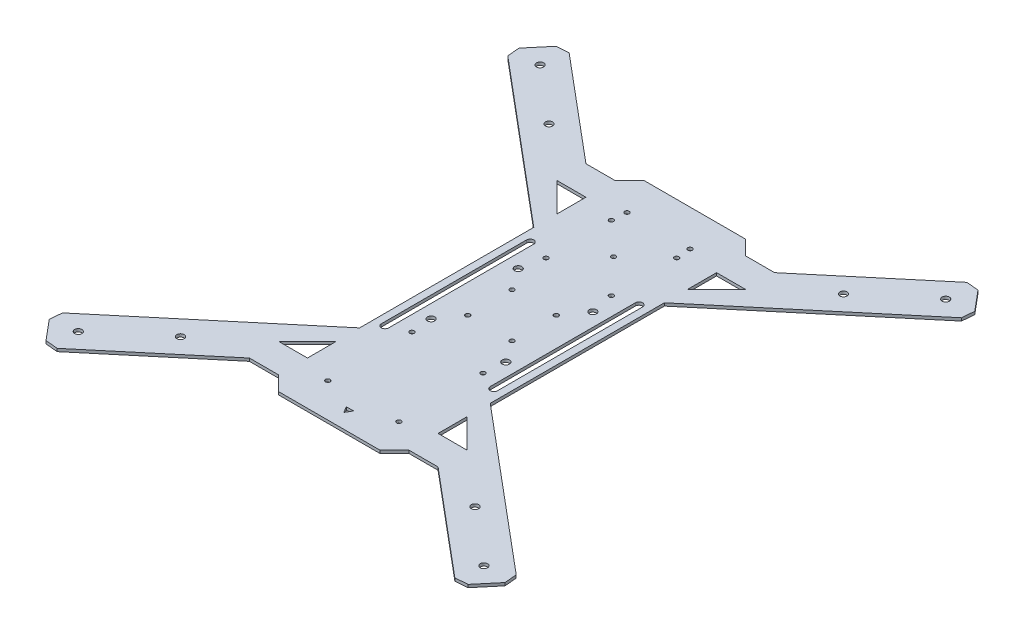
SolidWorks part; units mm, degrees
material "Thornel Mat VMA"
ref_plane "Ön Düzlem" through (0, 0, 0) normal (0, 0, 1) x (1, 0, 0)
ref_plane "Üst Düzlem" through (0, 0, 0) normal (0, 1, 0) x (1, 0, 0)
ref_plane "Sağ Düzlem" through (0, 0, 0) normal (1, 0, 0) x (0, 0, -1)
sketch "Çizim2" plane through (0, 0, 0) normal (0, 1, 0) x (1, 0, 0)
  line L0 (-45, 60) -> (-160.8881, 157.2416)
  line L1 (-45, 100) -> (45, 100)
  line L2 (-45, 100) -> (-45, -100)
  line L3 (-45, -100) -> (45, -100)
  line L4 (45, 100) -> (45, -100)
  line L5 (-160.8881, 157.2416) -> (-141.6044, 180.223)
  line L6 (-141.6044, 180.223) -> (-65, 115.9442)
  line L7 (-65, 115.9442) -> (-45, 115.9442)
  line L8 (-45, 115.9442) -> (-35, 125.9442)
  line L9 (-35, 125.9442) -> (35, 125.9442)
  line L10 (35, 125.9442) -> (45, 115.9442)
  line L11 (45, 115.9442) -> (65, 115.9442)
  line L12 (65, 115.9442) -> (141.6044, 180.223)
  line L13 (141.6044, 180.223) -> (160.8881, 157.2416)
  line L14 (160.8881, 157.2416) -> (45, 60)
  line L15 (0, 0) -> (-44.0753, 0) construction
  line L16 (160.8881, -157.2416) -> (45, -60)
  line L17 (141.6044, -180.223) -> (160.8881, -157.2416)
  line L18 (65, -115.9442) -> (141.6044, -180.223)
  line L19 (45, -115.9442) -> (65, -115.9442)
  line L20 (35, -125.9442) -> (45, -115.9442)
  line L21 (-35, -125.9442) -> (35, -125.9442)
  line L22 (-45, -115.9442) -> (-35, -125.9442)
  line L23 (-65, -115.9442) -> (-45, -115.9442)
  line L24 (-141.6044, -180.223) -> (-65, -115.9442)
  line L25 (-160.8881, -157.2416) -> (-141.6044, -180.223)
  line L26 (-45, -60) -> (-160.8881, -157.2416)
  dimension "D1" = 200
  dimension "D2" = 90
  dimension "D3" = 130
  dimension "D4" = 130
  dimension "D5" = 30
  dimension "D6" = 100
  dimension "D7" = 100
  dimension "D8" = 45
  dimension "D9" = 100
  dimension "D10" = 130
  dimension "D11" = 135
  dimension "D12" = 135
  dimension "D13" = 10
  dimension "D14" = 40
  dimension "D15" = 40
extrude "Yükseklik-Ekstrüzyon2" add sketch "Çizim2" along normal blind 2
sketch "Çizim3" plane through (0, 2, 0) normal (0, 1, 0) x (1, 0, 0)
  line L0 (-35, 125.9442) -> (35, 125.9442) construction
  circle A0 centre (-22.5, 90.9442) radius 1.55
  circle A1 centre (22.5, 90.9442) radius 1.55
  circle A2 centre (-22.5, 45.9442) radius 1.55
  circle A3 centre (22.5, 45.9442) radius 1.55
  circle A4 centre (-15.25, 15.25) radius 1.55
  circle A5 centre (15.25, 15.25) radius 1.55
  circle A6 centre (15.25, -15.25) radius 1.55
  circle A7 centre (-15.25, -15.25) radius 1.55
  dimension "D1" = 45
  dimension "D2" = 45
  dimension "D3" = 45
  dimension "D6" = 3.1
  dimension "D7" = 3.1
  dimension "D8" = 3.1
  dimension "D9" = 3.1
  dimension "D10" = 30.5
  dimension "D12" = 3.1
  dimension "D13" = 3.1
  dimension "D14" = 3.1
  dimension "D15" = 3.1
  dimension "D16" = 15.25
  dimension "D17" = 15.25
  dimension "D4" = 35
  dimension "D5" = 22.5
  dimension "D11" = 30.5
extrude "Kes-Ekstrüzyon1" cut sketch "Çizim3" against normal blind 2
sketch "Çizim4" plane through (0, 2, 0) normal (0, 1, 0) x (1, 0, 0)
  line L0 (-2.5, -111.6141) -> (0, -115.9442)
  line L1 (0, -115.9442) -> (2.5, -111.6141)
  line L2 (2.5, -111.6141) -> (-2.5, -111.6141)
  line L3 (-35, -125.9442) -> (35, -125.9442) construction
  dimension "D1" = 5
  dimension "D2" = 5
  dimension "D3" = 5
  dimension "D4" = 10
extrude "Kes-Ekstrüzyon2" cut sketch "Çizim4" against normal up to vertex (2 mm away) up to point (0, 0, 0)
sketch "Çizim5" plane through (0, 2, 0) normal (0, 1, 0) x (1, 0, 0)
  line L0 (-65, 95.9442) -> (-45, 95.9442)
  line L1 (-45, 95.9442) -> (-45, 75.9442)
  line L2 (-45, 75.9442) -> (-65, 95.9442)
  line L3 (-65, 115.9442) -> (-45, 115.9442) construction
  line L4 (0, 0) -> (0, 125.9442) construction
  line L5 (-35, 125.9442) -> (35, 125.9442) construction
  line L6 (0, 0) -> (-45, 0) construction
  line L7 (-45, 60) -> (-45, -60) construction
  line L8 (45, 75.9442) -> (65, 95.9442)
  line L9 (45, 95.9442) -> (45, 75.9442)
  line L10 (65, 95.9442) -> (45, 95.9442)
  line L11 (65, -95.9442) -> (45, -95.9442)
  line L12 (45, -95.9442) -> (45, -75.9442)
  line L13 (45, -75.9442) -> (65, -95.9442)
  line L14 (-45, -75.9442) -> (-65, -95.9442)
  line L15 (-45, -95.9442) -> (-45, -75.9442)
  line L16 (-65, -95.9442) -> (-45, -95.9442)
  dimension "D1" = 20
  dimension "D2" = 20
  dimension "D3" = 20
  dimension "D4" = 45
extrude "Kes-Ekstrüzyon3" cut sketch "Çizim5" against normal blind 20
chamfer "Pah1" distance 6 angle 45 8 edges at (160.8881, 1, -157.2416) (141.6044, 1, -180.223) (-141.6044, 1, -180.223) (-160.8881, 1, -157.2416) (-160.8881, 1, 157.2416) (-141.6044, 1, 180.223) (160.8881, 1, 157.2416) (141.6044, 1, 180.223)
sketch "Çizim6" plane through (0, 2, 0) normal (0, 1, 0) x (1, 0, 0)
  line L0 (-157.0313, 161.8379) -> (-145.4612, 175.6267) construction
  line L1 (-45, 60) -> (-156.2918, 153.3849) construction
  line L2 (0, 0) -> (0, 125.9442) construction
  line L3 (-35, 125.9442) -> (35, 125.9442) construction
  line L4 (0, 0) -> (-45, 0) construction
  line L5 (-45, 60) -> (-45, -60) construction
  line L6 (65, 115.9442) -> (137.0082, 176.3662) construction
  line L7 (145.4612, 175.6267) -> (157.0313, 161.8379) construction
  line L8 (-45, -60) -> (-156.2918, -153.3849) construction
  line L9 (-157.0313, -161.8379) -> (-145.4612, -175.6267) construction
  line L10 (156.2918, -153.3849) -> (45, -60) construction
  line L11 (145.4612, -175.6267) -> (157.0313, -161.8379) construction
  circle A0 centre (-139.7556, 159.0905) radius 2.5
  circle A1 centre (-101.4534, 126.9511) radius 2.5
  circle A8 centre (139.7556, 159.0905) radius 2.5
  circle A9 centre (101.4534, 126.9511) radius 2.5
  circle A10 centre (-139.7556, -159.0905) radius 2.5
  circle A11 centre (-101.4534, -126.9511) radius 2.5
  circle A12 centre (101.4534, -126.9511) radius 2.5
  circle A13 centre (139.7556, -159.0905) radius 2.5
  point P24 (151.2463, 168.7323)
  dimension "D1" = 5
  dimension "D2" = 5
  dimension "D3" = 15
  dimension "D4" = 50
  dimension "D5" = 15
  dimension "D6" = 15
  dimension "D7" = 15
  dimension "D8" = 15
  dimension "D9" = 5
  dimension "D10" = 5
  dimension "D11" = 50
  dimension "D12" = 15
  dimension "D13" = 50
  dimension "D14" = 15
  dimension "D15" = 15
  dimension "D16" = 5
  dimension "D17" = 5
  dimension "D18" = 15
  dimension "D19" = 5
  dimension "D20" = 5
  dimension "D21" = 15
  dimension "D22" = 15
  dimension "D23" = 50
  dimension "D24" = 15
extrude "Kes-Ekstrüzyon4" cut sketch "Çizim6" against normal blind 20
sketch "Çizim7" plane through (0, 2, 0) normal (0, 1, 0) x (1, 0, 0)
  line L0 (-35, -125.9442) -> (35, -125.9442) construction
  line L1 (-28, -125.9442) -> (28, -125.9442) construction
  line L2 (-28, -125.9442) -> (-28, -40.9442) construction
  line L3 (-28, -40.9442) -> (28, -40.9442) construction
  line L4 (28, -125.9442) -> (28, -40.9442) construction
  circle A0 centre (-24.5, -44.4442) radius 1.55
  circle A1 centre (-24.5, -102.4442) radius 1.55
  circle A2 centre (24.5, -102.4442) radius 1.55
  circle A3 centre (24.5, -44.4442) radius 1.55
  dimension "D3" = 49
  dimension "D4" = 3.1
  dimension "D5" = 3.1
  dimension "D8" = 3.1
  dimension "D9" = 3.1
  dimension "D1" = 85
  dimension "D2" = 56
  dimension "D6" = 3.5
  dimension "D7" = 3.5
  dimension "D10" = 58
  dimension "D11" = 28
extrude "Kes-Ekstrüzyon6" cut sketch "Çizim7" against normal blind 20
sketch "Çizim8" plane through (0, 2, 0) normal (0, 1, 0) x (1, 0, 0)
  line L0 (-35, 125.9442) -> (35, 125.9442) construction
  circle A0 centre (0, 69.9442) radius 1.55
  circle A1 centre (-21.75, 100.9442) radius 1.55
  circle A2 centre (21.75, 100.9442) radius 1.55
  dimension "D1" = 3.1
  dimension "D2" = 3.1
  dimension "D3" = 3.1
  dimension "D4" = 43.5
  dimension "D5" = 31
  dimension "D7" = 25
  dimension "D6" = 21.75
extrude "Kes-Ekstrüzyon7" cut sketch "Çizim8" against normal up to surface (2 mm away) up to face at (24.5, 0, 45.9942)
sketch "Çizim9" plane through (0, 2, 0) normal (0, 1, 0) x (1, 0, 0)
  line L0 (-37.5, 50) -> (-37.5, -50) construction
  line L1 (-35, 50) -> (-35, -50)
  line L2 (-40, 50) -> (-40, -50)
  line L3 (37.5, 50) -> (37.5, -50) construction
  line L4 (40, 50) -> (40, -50)
  line L5 (35, 50) -> (35, -50)
  arc A0 (-35, 50) -> (-40, 50) centre (-37.5, 50) ccw
  arc A1 (-40, -50) -> (-35, -50) centre (-37.5, -50) ccw
  arc A2 (40, 50) -> (35, 50) centre (37.5, 50) ccw
  arc A3 (35, -50) -> (40, -50) centre (37.5, -50) ccw
  point P2 (-37.5, 0)
  point P7 (37.5, 0)
  dimension "D5" = 5
  dimension "D1" = 5
  dimension "D2" = 50
  dimension "D3" = 50
  dimension "D4" = 35
  dimension "D6" = 35
  dimension "D7" = 50
  dimension "D8" = 50
extrude "Kes-Ekstrüzyon8" cut sketch "Çizim9" against normal blind 10
sketch "Çizim10" plane through (0, 2, 0) normal (0, 1, 0) x (1, 0, 0)
  line L0 (45, 60) -> (45, -60) construction
  line L1 (0, 0) -> (0, 125.9442) construction
  line L2 (-35, 125.9442) -> (35, 125.9442) construction
  line L3 (0, 0) -> (-45, 0) construction
  line L4 (-45, 60) -> (-45, -60) construction
  circle A0 centre (25.75, -30) radius 2.5
  circle A1 centre (-25.75, -30) radius 2.5
  circle A2 centre (25.75, 30) radius 2.5
  circle A3 centre (-25.75, 30) radius 2.5
  dimension "D1" = 5
  dimension "D2" = 30
  dimension "D3" = 19.25
extrude "Kes-Ekstrüzyon9" cut sketch "Çizim10" against normal blind 10
